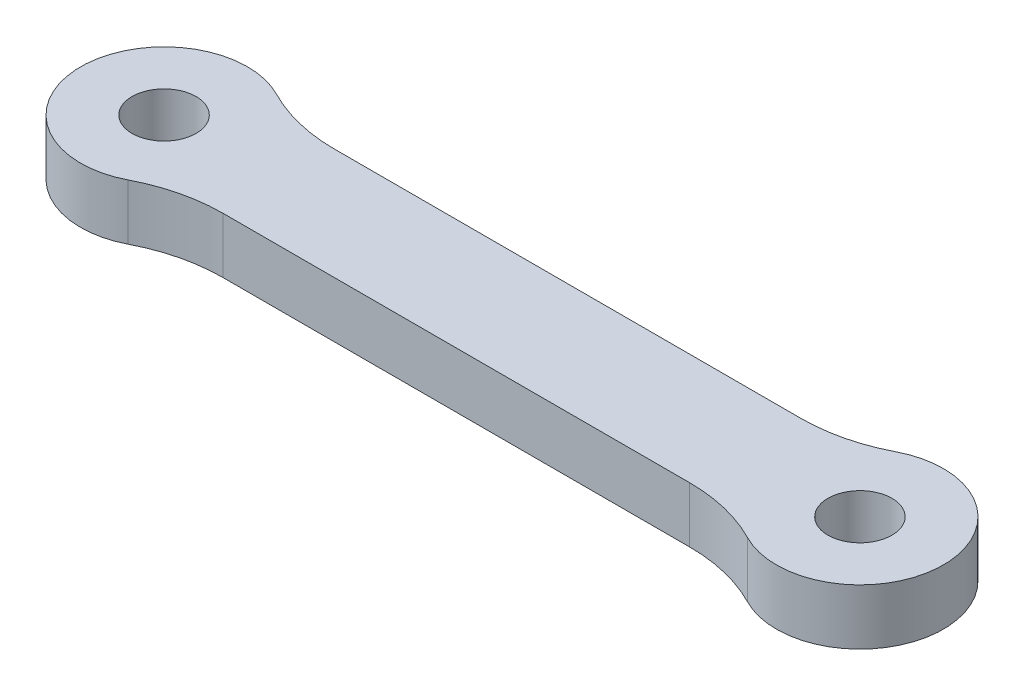
SolidWorks part; units mm, degrees
ref_plane "Спереди" through (0, 0, 0) normal (0, 0, 1) x (1, 0, 0)
ref_plane "Сверху" through (0, 0, 0) normal (0, 1, 0) x (1, 0, 0)
ref_plane "Справа" through (0, 0, 0) normal (1, 0, 0) x (0, 0, -1)
sketch "Эскиз1" plane through (0, 0, 0) normal (0, 1, 0) x (1, 0, 0)
  line L0 (0, 0) -> (25, 0) construction
  line L1 (2.2361, 2) -> (22.7639, 2)
  line L3 (22.7639, -2) -> (2.2361, -2)
  circle A0 centre (0, 0) radius 1.15
  arc A1 (2.2361, 2) -> (2.2361, -2) centre (0, 0) ccw
  circle A2 centre (25, 0) radius 1.15
  arc A3 (22.7639, -2) -> (22.7639, 2) centre (25, 0) ccw
  dimension "D4" = 2.3
  dimension "D5" = 2.3
  dimension "D6" = 6
  dimension "D7" = 6
  dimension "D1" = 25
  dimension "D2" = 2
  dimension "D3" = 2
extrude "Бобышка-Вытянуть1" add sketch "Эскиз1" along normal blind 2
fillet "Скругление1" radius 6 4 edges at (22.7639, 1, -2) (22.7639, 1, 2) (2.2361, 1, 2) (2.2361, 1, -2)
